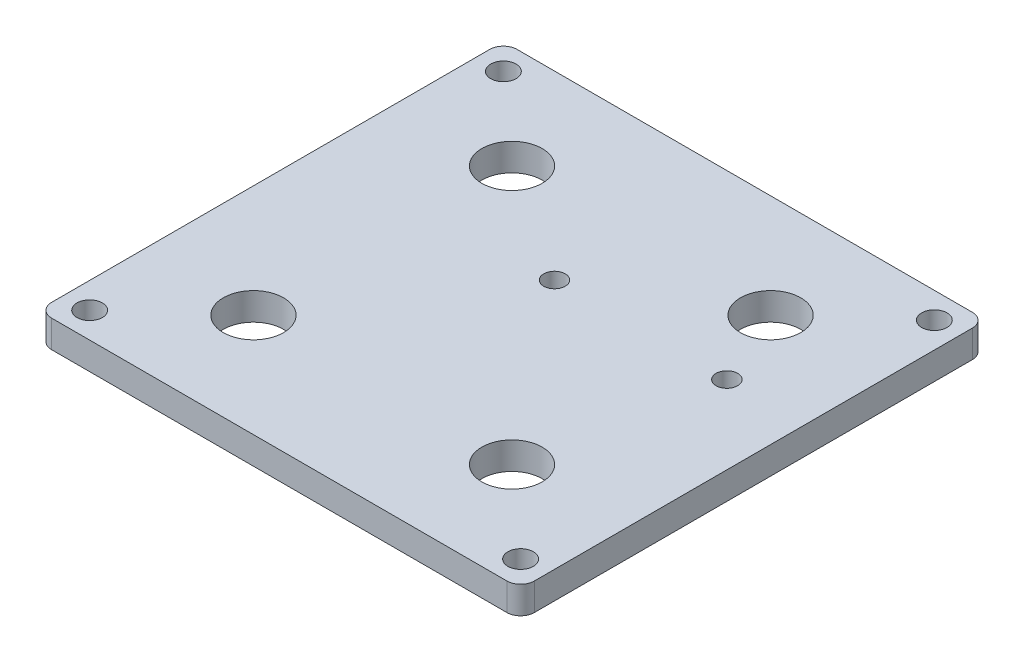
SolidWorks part; units mm, degrees
material "AISI 4130 Steel, annealed at 865C"
ref_plane "Front Plane" through (0, 0, 0) normal (0, 0, 1) x (1, 0, 0)
ref_plane "Top Plane" through (0, 0, 0) normal (0, 1, 0) x (1, 0, 0)
ref_plane "Right Plane" through (0, 0, 0) normal (1, 0, 0) x (0, 0, -1)
sketch "Sketch1" plane through (0, 0, 0) normal (0, 1, 0) x (1, 0, 0)
  line L0 (7, -7) -> (7, -37) construction
  line L1 (0, 0) -> (44, 0)
  line L2 (0, 0) -> (0, -44)
  line L3 (0, -44) -> (44, -44)
  line L4 (44, 0) -> (44, -44)
  line L5 (37, -7) -> (7, -7) construction
  line L6 (20.93, -16) -> (40.93, -16) construction
  line L7 (22, 0) -> (22, -44) construction
  line L8 (44, 0) -> (51.18, 0)
  line L9 (51.18, 0) -> (51.18, -44)
  line L10 (51.18, -44) -> (44, -44)
  line L11 (22, -22) -> (-15.2405, -22) construction
  line L12 (40, 2.5) -> (40, 0) construction
  line L13 (0, 0) -> (44, 0)
  line L14 (0, 0) -> (0, 5)
  line L15 (0, 5) -> (44, 5)
  line L16 (44, 0) -> (44, 5)
  line L17 (0, -44) -> (44, -44)
  line L18 (0, -44) -> (0, -49)
  line L19 (0, -49) -> (44, -49)
  line L20 (44, -44) -> (44, -49)
  line L21 (40, -46.5) -> (40, -44) construction
  circle A0 centre (7, -7) radius 3.5
  circle A1 centre (37, -7) radius 3.5
  circle A2 centre (37, -37) radius 3.5
  circle A3 centre (7, -37) radius 3.5
  circle A4 centre (20.93, -16) radius 0.5
  circle A5 centre (40.93, -16) radius 0.5
  circle A6 centre (4, 2.5) radius 0.5 construction
  circle A7 centre (40, 2.5) radius 0.5 construction
  circle A8 centre (40, -46.5) radius 0.5 construction
  circle A9 centre (4, -46.5) radius 0.5 construction
  dimension "D1" = 7
  dimension "D2" = 1
  dimension "D14" = 1
  dimension "D3" = 30
  dimension "D4" = 30
  dimension "D5" = 20
  dimension "D6" = 44
  dimension "D7" = 44
  dimension "D8" = 7
  dimension "D9" = 7
  dimension "D10" = 1.07
  dimension "D11" = 7.18
  dimension "D12" = 6
  dimension "D13" = 5
  dimension "D15" = 4
  dimension "D16" = 4
  dimension "D17" = 2.5
extrude "Boss-Extrude1" add sketch "Sketch1" along normal blind 3.175 contours L4 L1 L2 L3 A5 A4 A3 A2 A1 A0 | L1 L16 L15 L14 | L20 L3 L18 L19
sketch "Sketch3" plane through (0, 3.175, 0) normal (0, 1, 0) x (1, 0, 0)
  line L0 (44, 5) -> (44, -49) construction
  line L1 (0, 5) -> (-6, 5)
  line L2 (0, 5) -> (0, -49)
  line L3 (0, -49) -> (-6, -49)
  line L4 (-6, 5) -> (-6, -49)
  line L5 (44, 5) -> (50, 5)
  line L6 (44, 5) -> (44, -49)
  line L7 (44, -49) -> (50, -49)
  line L8 (50, 5) -> (50, -49)
  circle A0 centre (-3, 2) radius 1.4732
  circle A1 centre (-3, -46) radius 1.4732
  circle A2 centre (47, -46) radius 1.4732
  circle A3 centre (47, 2) radius 1.4732
  point P10 (-3, -46)
  point P12 (47, -46)
  point P14 (-3, 2)
  point P15 (47, 2)
  point P24 (0, 0)
  point P25 (0, 0)
  point P26 (44, 0)
  point P27 (-3, -46)
  point P29 (44, -44)
  point P31 (0, 0)
  point P32 (0, 0)
  point P33 (0, -49)
  point P35 (0, 0)
  point P36 (0, 0)
  point P37 (0, 5)
  point P39 (44, 5)
  dimension "D6" = 2.9464
  dimension "D1" = 6
  dimension "D2" = 3
  dimension "D3" = 3
  dimension "D4" = 3
  dimension "D5" = 3
extrude "Boss-Extrude2" add sketch "Sketch3" against normal up to surface (3.175 mm away) up to face at (22, 0, 22)
hole_wizard "M3x0.5 Tapped Hole1" positions "3DSketch1" profile "Sketch2" tap size "M3x0.5" standard "ANSI Metric" end condition through all
sketch3d "3DSketch1"
  circle A2 centre (40.93, 3.175, 16) radius 0.5 construction
  circle A3 centre (20.93, 3.175, 16) radius 0.5 construction
  point P0 (40.93, 3.175, 16)
  point P2 (20.93, 3.175, 16)
  point P17 (40.93, 3.675, 16)
  point P25 (20.93, 3.675, 16)
sketch "Sketch2" plane through (40.93, 3.175, 16) normal (1, 0, 0) x (0, 0, 1)
  line L0 (0, 0) -> (0, 3.175)
  line L1 (0, 3.175) -> (1.25, 3.175)
  line L2 (1.25, 3.175) -> (1.25, 0)
  line L5 (1.25, 0) -> (0, 0)
  line L11 (0, -6.35) -> (0, 107.95) construction
  dimension "Thru Tap Drill Dia." = 2.5
  dimension "Thru Tap Drill Depth" = 3.175
cosmetic thread "Hole Thread9" parameters "D2"=3
cosmetic thread "Hole Thread10" parameters "D2"=3
fillet "Fillet1" radius 1.5875 4 edges at (50, 1.5875, -5) (50, 1.5875, 49) (-6, 1.5875, 49) (-6, 1.5875, -5)
equation "\"D8@Sketch1\"=(\"D7@Sketch1\"-\"D4@Sketch1\")/2"
equation "\"D9@Sketch1\"=\"D8@Sketch1\""
equation "\"D10@Sketch1\"=9.37mm-6.3-2-0.14+0.58-0.44"
equation "\"D3@Sketch3\"=\"D2@Sketch3\""
equation "\"D4@Sketch3\"=\"D3@Sketch3\""
equation "\"D5@Sketch3\"=\"D2@Sketch3\""
equation "\"D16@Sketch1\"=\"D15@Sketch1\""
equation "\"D17@Sketch1\"=\"D13@Sketch1\"/2"
